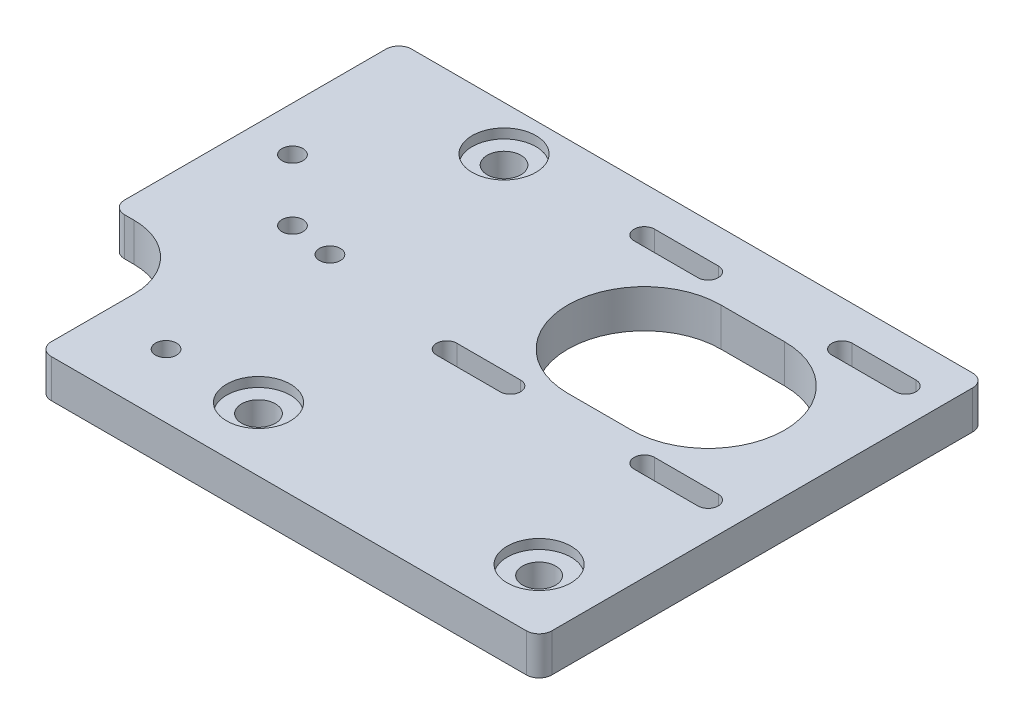
SolidWorks part; units mm, degrees
material "6061 Alloy"
ref_plane "Front" through (0, 0, 0) normal (0, 0, 1) x (1, 0, 0)
ref_plane "Top" through (0, 0, 0) normal (0, 1, 0) x (1, 0, 0)
ref_plane "Right" through (0, 0, 0) normal (1, 0, 0) x (0, 0, -1)
sketch "Sketch3" plane through (0, 0, 0) normal (0, 1, 0) x (1, 0, 0)
  line L0 (20, 70) -> (20, 20) construction
  line L1 (0, 0) -> (78.5, 0)
  line L2 (0, 0) -> (0, 70) construction
  line L3 (0, 70) -> (78.5, 70)
  line L4 (78.5, 0) -> (78.5, 70)
  line L5 (20, 20) -> (78.5, 20) construction
  line L6 (10, 70) -> (10, 10) construction
  line L7 (10, 10) -> (78.5, 10) construction
  line L8 (0, 70) -> (-13.5, 70)
  line L11 (-13.5, 70) -> (-13.5, 25)
  line L12 (-13.5, 25) -> (0, 25)
  line L14 (47.5, 47.5) -> (57.5, 47.5) construction
  line L15 (47.5, 59.5) -> (57.5, 59.5)
  line L16 (47.5, 35.5) -> (57.5, 35.5)
  line L17 (32, 63) -> (42, 63) construction
  line L18 (37, 32) -> (68, 32) construction
  line L19 (37, 32) -> (37, 63) construction
  line L20 (37, 63) -> (68, 63) construction
  line L21 (68, 32) -> (68, 63) construction
  line L22 (37, 32) -> (68, 63) construction
  line L23 (37, 63) -> (68, 32) construction
  line L24 (32, 64.6) -> (42, 64.6)
  line L25 (32, 61.4) -> (42, 61.4)
  line L26 (63, 63) -> (73, 63) construction
  line L27 (63, 64.6) -> (73, 64.6)
  line L28 (63, 61.4) -> (73, 61.4)
  line L29 (63, 32) -> (73, 32) construction
  line L30 (63, 33.6) -> (73, 33.6)
  line L31 (63, 30.4) -> (73, 30.4)
  line L32 (32, 32) -> (42, 32) construction
  line L33 (32, 33.6) -> (42, 33.6)
  line L34 (32, 30.4) -> (42, 30.4)
  line L35 (24.9094, 47.5) -> (47.5, 47.5) construction
  line L36 (73, 63) -> (78.5, 63) construction
  line L37 (32, 63) -> (20, 63) construction
  line L38 (-6.5, 64.325) -> (-6.5, 46.325) construction
  line L39 (10, 35.7) -> (10, 64.325) construction
  line L40 (10, 64.325) -> (-6.5, 64.325) construction
  line L44 (0, 25) -> (0, 0)
  circle A0 centre (10, 56) radius 2.6
  circle A1 centre (10, 10) radius 2.6
  circle A2 centre (68.5, 10) radius 2.6
  arc A3 (47.5, 59.5) -> (47.5, 35.5) centre (47.5, 47.5) ccw
  arc A4 (57.5, 35.5) -> (57.5, 59.5) centre (57.5, 47.5) ccw
  arc A5 (32, 64.6) -> (32, 61.4) centre (32, 63) ccw
  arc A6 (42, 61.4) -> (42, 64.6) centre (42, 63) ccw
  arc A7 (63, 64.6) -> (63, 61.4) centre (63, 63) ccw
  arc A8 (73, 61.4) -> (73, 64.6) centre (73, 63) ccw
  arc A9 (63, 33.6) -> (63, 30.4) centre (63, 32) ccw
  arc A10 (73, 30.4) -> (73, 33.6) centre (73, 32) ccw
  arc A11 (32, 33.6) -> (32, 30.4) centre (32, 32) ccw
  arc A12 (42, 30.4) -> (42, 33.6) centre (42, 32) ccw
  circle A13 centre (10, 35.7) radius 2.7 construction
  circle A14 centre (-6.5, 46.325) radius 2.7 construction
  circle A15 centre (10, 10) radius 4.5 construction
  circle A16 centre (10, 64.325) radius 1.6 construction
  circle A17 centre (-6.5, 64.325) radius 1.6 construction
  circle A18 centre (30, 10) radius 2.6
  point P21 (52.5, 47.5)
  point P26 (52.5, 47.5)
  point P33 (37, 63)
  point P39 (68, 63)
  point P46 (68, 32)
  point P53 (37, 32)
  dimension "D7" = 5.2
  dimension "D10" = 12
  dimension "D12" = 1.6
  dimension "D15" = 10
  dimension "D17" = 18
  dimension "D18" = 7
  dimension "D20" = 2.35
  dimension "D21" = 5.4
  dimension "D22" = 9
  dimension "D23" = 3.2
  dimension "D25" = 5.5
  dimension "D26" = 20
  dimension "D16" = 10.625
  dimension "D8" = 14
  dimension "D9" = 10.7
  dimension "D1" = 70
  dimension "D2" = 10
  dimension "D3" = 20
  dimension "D4" = 20
  dimension "D5" = 10
  dimension "D6" = 10
  dimension "D11" = 31
  dimension "D13" = 10
  dimension "D14" = 12
  dimension "D19" = 16.5
  dimension "D24" = 22.5
extrude "Boss-Extrude1" add sketch "Sketch3" along normal blind 6
sketch "Sketch5" plane through (0, 6, 0) normal (0, 1, 0) x (1, 0, 0)
  circle A0 centre (10, 56) radius 5
  circle A1 centre (10, 10) radius 5
  circle A2 centre (30, 10) radius 5
  circle A3 centre (68.5, 10) radius 5
  dimension "D1" = 10
fillet "Fillet1" radius 10 1 edges at (0, 3, -25)
sketch "Sketch7" plane through (0, 6, 0) normal (0, 1, 0) x (1, 0, 0)
  line L0 (-6.5, 64.325) -> (10, 64.325) construction
  line L1 (-6.5, 67.325) -> (10, 67.325) construction
  line L2 (-6.5, 61.325) -> (10, 61.325) construction
  arc A0 (-6.5, 67.325) -> (-6.5, 61.325) centre (-6.5, 64.325) ccw construction
  arc A1 (10, 61.325) -> (10, 67.325) centre (10, 64.325) ccw construction
  circle A2 centre (-6.5, 64.325) radius 1.35
  circle A3 centre (10, 64.325) radius 1.35
  point P2 (1.75, 64.325)
  dimension "D1" = 3
  dimension "D2" = 2.7
hole_wizard "M3 Clearance Hole1" positions "Sketch8" profile "Sketch9" hole size "M3" standard "ANSI Metric" end condition through all
sketch "Sketch8" plane through (0, 6, 0) normal (0, 1, 0) x (1, 0, 0)
  point P0 (10, 64.325)
  point P3 (-6.5, 64.325)
sketch "Sketch9" plane through (10, 6, -64.325) normal (1, 0, 0) x (0, 0, 1)
  line L0 (0, 0) -> (0, 6)
  line L1 (0, 6) -> (1.6, 6)
  line L2 (1.6, 6) -> (1.6, 0)
  line L5 (1.6, 0) -> (0, 0)
  line L11 (0, -6.35) -> (0, 107.95) construction
  dimension "Thru Hole Dia." = 3.2
  dimension "Thru Hole Depth" = 6
hole_wizard "M4x0.7 Tapped Hole1" positions "Sketch10" profile "Sketch11" tap size "M4x0.7" standard "ANSI Metric" end condition through all
sketch "Sketch10" plane through (0, 6, 0) normal (0, 1, 0) x (1, 0, 0)
  circle A0 centre (15.65, 30.05) radius 11.5
  point P0 (-6.5, 46.325)
  point P3 (10, 35.7)
  dimension "D3" = 23
  dimension "D1" = 5.65
  dimension "D2" = 5.65
sketch "Sketch11" plane through (-6.5, 6, -46.325) normal (1, 0, 0) x (0, 0, 1)
  line L0 (0, 0) -> (0, 6)
  line L1 (0, 6) -> (1.65, 6)
  line L2 (1.65, 6) -> (1.65, 0)
  line L5 (1.65, 0) -> (0, 0)
  line L11 (0, -6.35) -> (0, 107.95) construction
  dimension "Thru Tap Drill Dia." = 3.3
  dimension "Thru Tap Drill Depth" = 6
cosmetic thread "Hole Thread1" parameters "D2"=4
cosmetic thread "Hole Thread2" parameters "D2"=4
fillet "Fillet2" radius 2 5 edges at (-13.5, 3, -25) (0, 3, 0) (-13.5, 3, -70) (78.5, 3, 0) (78.5, 3, -70)
sketch "Sketch12" [suppressed] plane through (0, 6, 0) normal (0, 1, 0) x (1, 0, 0)
  circle A4 centre (10, 35.7) radius 2.65
  circle A5 centre (-6.5, 46.325) radius 2.65
  circle A6 centre (-6.5, 46.325) radius 5
  circle A7 centre (10, 35.7) radius 5
  dimension "D1" = 10
  dimension "D2" = 5.3
extrude "Counterbore" cut sketch "Sketch5" against normal blind 1.5
mirror "Mirror1" [suppressed]
delete or keep bodies "Body-Delete/Keep 1" [suppressed] type delete bodies bodies 118
sketch "Sketch13" [suppressed] plane through (0, 6, 0) normal (0, 1, 0) x (1, 0, 0)
  line L0 (109.5, 52.595) -> (163.5, 52.595) construction
  line L1 (106.7531, 43.2089) -> (150.3804, 15.2807) construction
  line L2 (97.1501, 42.9793) -> (149.8919, 15.5633) construction
  line L3 (169.77, 46.325) -> (169.77, 16.6625) construction
  circle A0 centre (109.5, 47.5) radius 5.095
  circle A1 centre (147, 10) radius 6.27
  circle A2 centre (163.5, 46.325) radius 6.27
  circle A3 centre (99.5, 47.5) radius 5.095
  circle A4 centre (157.04, 39.865) radius 12.73
  circle A5 centre (153.855, 36.68) radius 15.915
  dimension "D1" = 32.626
  dimension "D2" = 10.19
  dimension "D3" = 27.466
  dimension "D4" = 12.54
  dimension "D5" = 25.46
  dimension "D6" = 31.83
sketch "Sketch14" plane through (0, 6, 0) normal (0, 1, 0) x (1, 0, 0)
  circle A0 centre (10, 10) radius 5 construction
  circle A1 centre (10, 10) radius 5
  circle A4 centre (10, 56) radius 5 construction
  circle A5 centre (10, 56) radius 5
  circle A6 centre (-6.5, 64.325) radius 1.6 construction
  circle A7 centre (10, 64.325) radius 1.6 construction
  circle A8 centre (-6.5, 64.325) radius 1.6
  circle A9 centre (10, 64.325) radius 1.6
  circle A10 centre (30, 10) radius 5 construction
  circle A11 centre (30, 10) radius 5
extrude "Hole Filler" add sketch "Sketch14" against normal up to surface (6 mm away) up to face at (-6.5, 0, -44.675)
sketch "Pulley Layout" plane through (0, 6, 0) normal (0, 1, 0) x (1, 0, 0)
  line L0 (-6.5, 52.595) -> (47.5, 52.595) construction
  line L1 (50.2469, 43.2089) -> (6.6196, 15.2807) construction
  line L2 (59.8499, 42.9793) -> (7.1081, 15.5633) construction
  line L3 (-12.77, 46.325) -> (-12.77, 14.797) construction
  line L4 (48.9376, 52.388) -> (14.1553, 62.6176) construction
  circle A0 centre (10, 10) radius 6.27
  circle A1 centre (47.5, 47.5) radius 5.095
  circle A2 centre (57.5, 47.5) radius 5.095
  circle A3 centre (-6.5, 46.325) radius 6.27
  circle A4 centre (-0.04, 39.865) radius 12.73
  circle A5 centre (3.145, 36.68) radius 15.915
  circle A6 centre (10, 10) radius 9 construction
  circle A8 centre (8.23, 42.4709) radius 21
  circle A9 centre (3.145, 36.68) radius 18 construction
  dimension "D1" = 10.19
  dimension "D2" = 32.626
  dimension "D4" = 42
  dimension "40T Idler PD" = 25.46
  dimension "50T Idler PD" = 31.83
  dimension "D5" = 18
  dimension "D6" = 36
  dimension "D3" = 27.466
sketch "M5 hole relocation option" plane through (0, 6, 0) normal (0, 1, 0) x (1, 0, 0)
  line L0 (10, 10) -> (78.5, 10) construction
  line L1 (76.5, 70) -> (-11.5, 70) construction
  line L2 (10, 63) -> (10, 10) construction
  circle A0 centre (24.5, 10) radius 2.6 construction
  circle A1 centre (10, 10) radius 9 construction
  circle A2 centre (30, 10) radius 2.6 construction
  circle A3 centre (24.5, 10) radius 5
  circle A4 centre (68.5, 10) radius 2.6 construction
  circle A5 centre (10, 63) radius 5
  dimension "D1" = 18
  dimension "D2" = 10
  dimension "D3" = 44
  dimension "D4" = 10
  dimension "D5" = 7
extrude "Cut-Extrude1" cut sketch "M5 hole relocation option" against normal blind 1.5
hole_wizard "M5 Clearance Hole1" positions "Sketch17" profile "Sketch19" hole size "M5" standard "ANSI Metric" end condition through all
sketch "Sketch17" plane through (0, 4.5, 0) normal (0, 1, 0) x (1, 0, 0)
  point P0 (24.5, 10)
  point P3 (10, 63)
sketch "Sketch19" plane through (24.5, 4.5, -10) normal (1, 0, 0) x (0, 0, 1)
  line L0 (0, 0) -> (0, 4.5)
  line L1 (0, 4.5) -> (2.65, 4.5)
  line L2 (2.65, 4.5) -> (2.65, 0)
  line L5 (2.65, 0) -> (0, 0)
  line L11 (0, -6.35) -> (0, 107.95) construction
  dimension "Thru Hole Dia." = 5.3
  dimension "Thru Hole Depth" = 4.5
hole_wizard "M4x0.7 Tapped Hole2" positions "Sketch21" profile "Sketch22" tap size "M4x0.7" standard "ANSI Metric" end condition through all
sketch "Sketch21" plane through (0, 6, 0) normal (0, 1, 0) x (1, 0, 0)
  point P0 (10, 10)
  point P4 (3.145, 36.68)
sketch "Sketch22" plane through (10, 6, -10) normal (1, 0, 0) x (0, 0, 1)
  line L0 (0, 0) -> (0, 6)
  line L1 (0, 6) -> (1.65, 6)
  line L2 (1.65, 6) -> (1.65, 0)
  line L5 (1.65, 0) -> (0, 0)
  line L11 (0, -6.35) -> (0, 107.95) construction
  dimension "Thru Tap Drill Dia." = 3.3
  dimension "Thru Tap Drill Depth" = 6
cosmetic thread "Hole Thread3" parameters "D2"=4
cosmetic thread "Hole Thread4" parameters "D2"=4
mirror "Mirror2" [suppressed]
delete or keep bodies "Body-Delete/Keep 2" [suppressed] type keep bodies bodies 123
